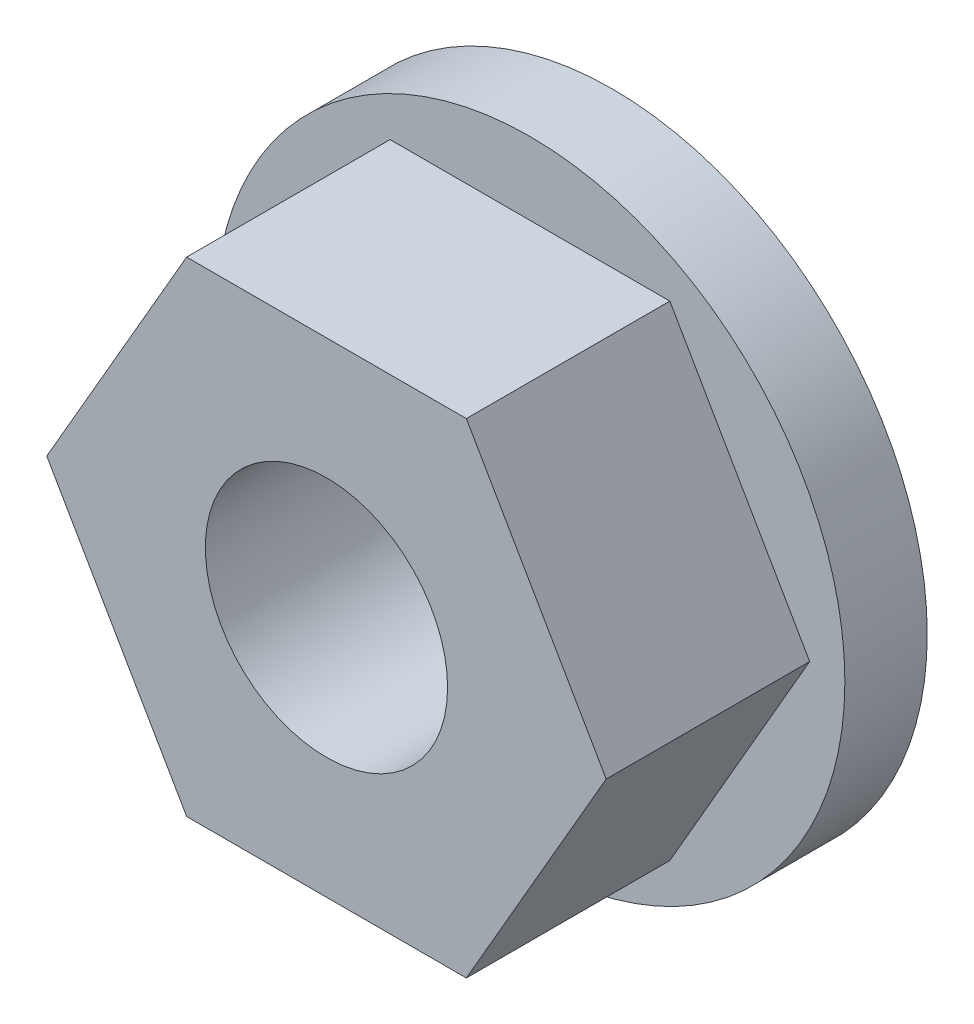
SolidWorks part; units mm, degrees
ref_plane "Спереди" through (0, 0, 0) normal (0, 0, 1) x (1, 0, 0)
ref_plane "Сверху" through (0, 0, 0) normal (0, 1, 0) x (1, 0, 0)
ref_plane "Справа" through (0, 0, 0) normal (1, 0, 0) x (0, 0, -1)
sketch "Эскиз1" plane through (0, 0, 0) normal (0, 0, 1) x (1, 0, 0)
  circle A0 centre (0, 0) radius 6.5
  dimension "D1" = 13
extrude "Бобышка-Вытянуть1" add sketch "Эскиз1" along normal blind 1.7
sketch "Эскиз2" plane through (0, 0, 1.7) normal (0, 0, 1) x (1, 0, 0)
  line L1 (5.7735, 0) -> (2.8868, 5)
  line L2 (2.8868, 5) -> (-2.8868, 5)
  line L3 (-2.8868, 5) -> (-5.7735, 0)
  line L4 (-5.7735, 0) -> (-2.8868, -5)
  line L5 (-2.8868, -5) -> (2.8868, -5)
  line L6 (2.8868, -5) -> (5.7735, 0)
  circle A0 centre (0, 0) radius 5 construction
  dimension "D1" = 10
extrude "Бобышка-Вытянуть2" add sketch "Эскиз2" along normal offset from surface (4.2 mm away) 5.9 up to face at (6.5, 0, 0)
sketch "Эскиз3" plane through (0, 0, 5.9) normal (0, 0, 1) x (1, 0, 0)
  circle A0 centre (0, 0) radius 2.5
  dimension "D1" = 5
extrude "Вырез-Вытянуть1" cut sketch "Эскиз3" against normal through all
